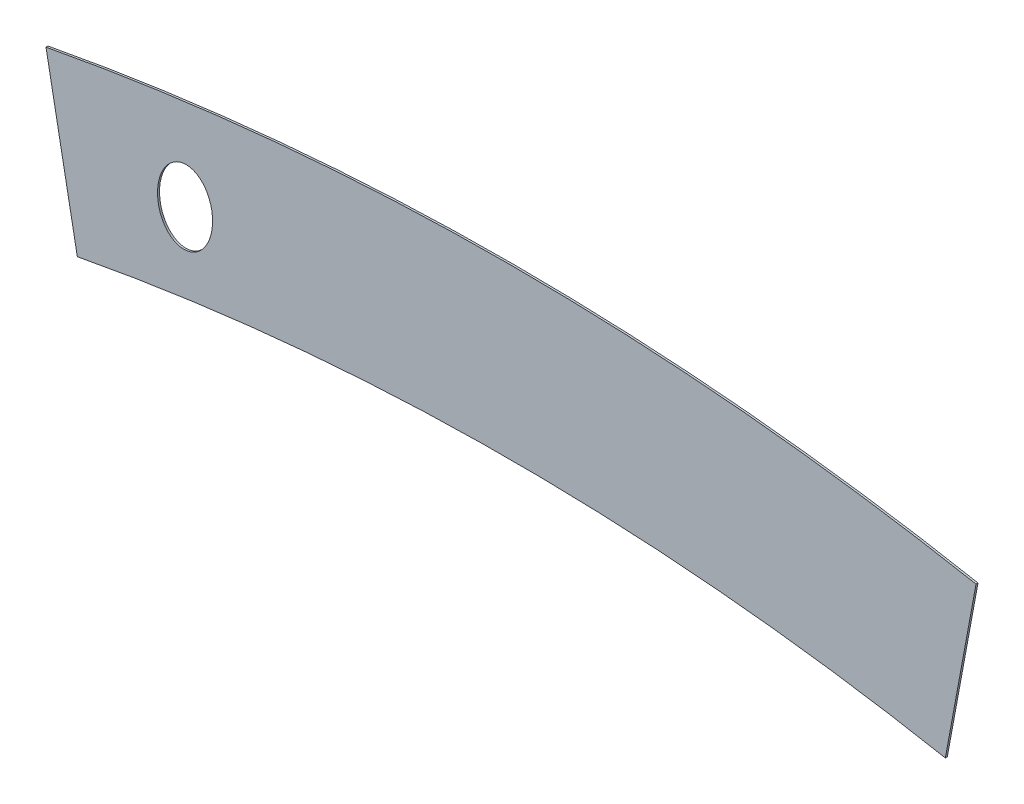
SolidWorks part; units mm, degrees
material "6061 Alloy"
ref_plane "front" through (0, 0, 0) normal (0, 0, 1) x (1, 0, 0)
ref_plane "top" through (0, 0, 0) normal (0, 1, 0) x (1, 0, 0)
ref_plane "right" through (0, 0, 0) normal (1, 0, 0) x (0, 0, -1)
sketch "Sketch1" plane through (0, 0, 0) normal (0, 0, 1) x (1, 0, 0)
  line L0 (0, 0) -> (0, -273.05) construction
  line L1 (0, 0) -> (383.281, 0) construction
  line L2 (-752.475, -70.7735) -> (-701.7766, -339.0756)
  line L3 (752.475, -70.7735) -> (702.818, -339.2735)
  line L4 (-517.525, -33.3212) -> (-536.0458, -311.4306) construction
  arc A0 (752.475, -70.7735) -> (-752.475, -70.7735) centre (0, -4035.6028) ccw
  arc A1 (702.818, -339.2735) -> (-701.7766, -339.0756) centre (0, -4035.6028) ccw
  ellipse E0 centre (-527.4407, -182.2164) end of major axis (-531.4492, -242.4081) minor radius 44.45
  dimension "D1" = 4035.6028
  dimension "D5" = 3.81
  dimension "D7" = 88.9
  dimension "D2" = 1504.95
  dimension "D3" = 273.05
  dimension "D4" = 701.7766
  dimension "D6" = 517.525
  dimension "D8" = 120.65
  dimension "D9" = 149.225
  dimension "D10" = 752.475
  dimension "D13" = 702.818
extrude "Base-Extrude" add sketch "Sketch1" against normal blind 3.175
